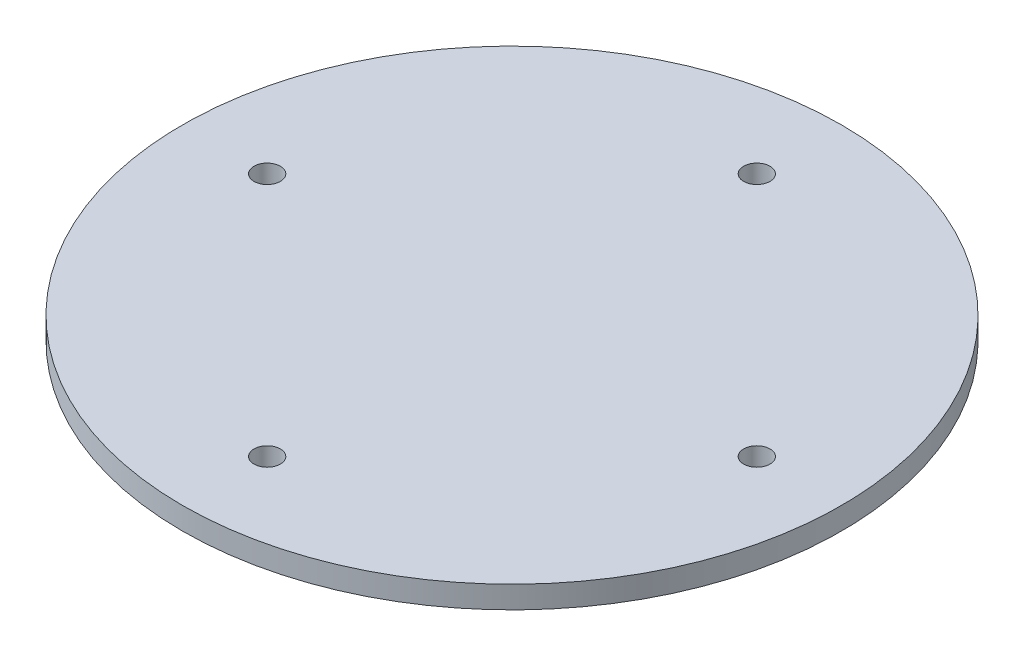
SolidWorks part; units mm, degrees
ref_plane "Front Plane" through (0, 0, 0) normal (0, 0, 1) x (1, 0, 0)
ref_plane "Top Plane" through (0, 0, 0) normal (0, 1, 0) x (1, 0, 0)
ref_plane "Right Plane" through (0, 0, 0) normal (1, 0, 0) x (0, 0, -1)
sketch "Sketch1" plane through (0, 0, 0) normal (0, 1, 0) x (1, 0, 0)
  circle A0 centre (0, 0) radius 44.45
  dimension "D1" = 88.9
extrude "Boss-Extrude1" add sketch "Sketch1" along normal blind 3
sketch "Sketch3" plane through (0, 3, 0) normal (0, 1, 0) x (1, 0, 0)
  line L0 (0, 0) -> (33.02, 0) construction
  circle A0 centre (33.02, 0) radius 1.778
  dimension "D1" = 3.556
  dimension "D2" = 33.02
extrude "Cut-Extrude1" cut sketch "Sketch3" against normal through all
pattern_circular "CirPattern1" count 4 over 360 about axis through (0, 0, 0) along (0, 1, 0) of "Cut-Extrude1"
sketch "Sketch4" plane through (0, 3, 0) normal (0, 1, 0) x (1, 0, 0)
  line L0 (-2.5981, 1.5) -> (2.5981, 1.5)
  arc A0 (-2.5981, 1.5) -> (2.5981, 1.5) centre (0, 0) ccw
  dimension "D1" = 6
  dimension "D2" = 1.5
extrude "Cut-Extrude2" [suppressed] cut sketch "Sketch4" against normal through all
